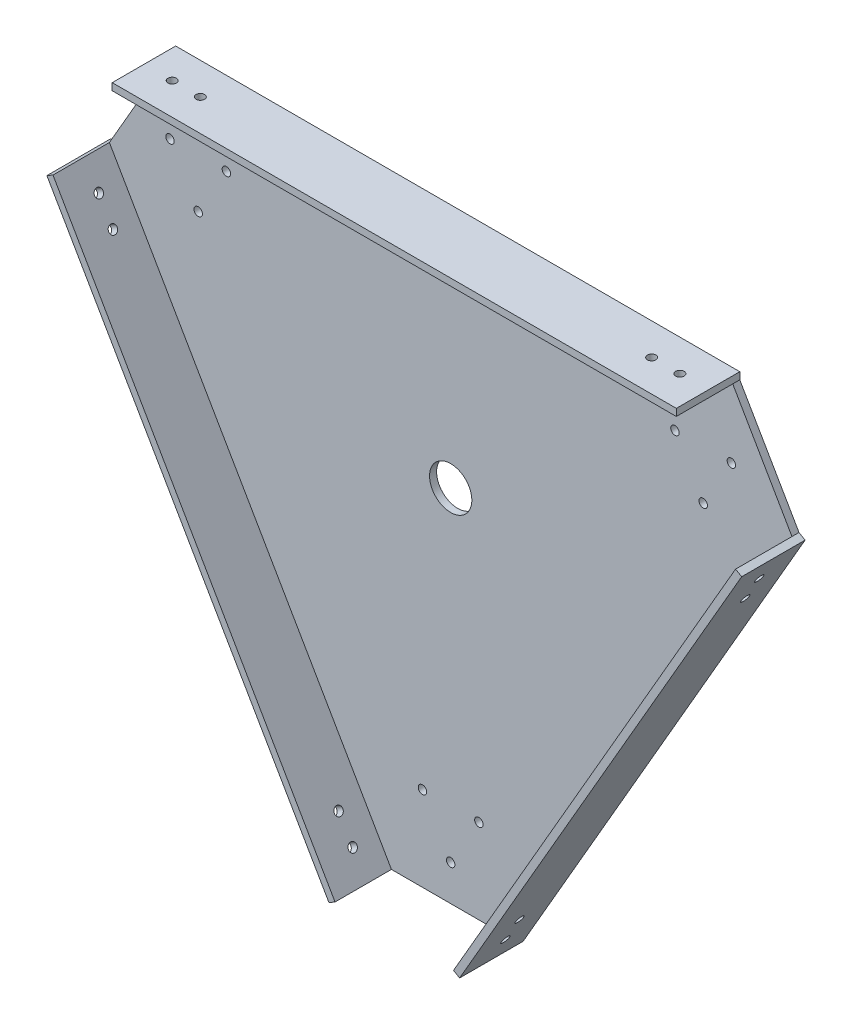
SolidWorks part; units mm, degrees
ref_plane "Спереди" through (0, 0, 0) normal (0, 0, 1) x (1, 0, 0)
ref_plane "Сверху" through (0, 0, 0) normal (0, 1, 0) x (1, 0, 0)
ref_plane "Справа" through (0, 0, 0) normal (1, 0, 0) x (0, 0, -1)
sketch "Эскиз1" plane through (0, 0, 0) normal (0, 0, 1) x (1, 0, 0)
  line L0 (0, 0) -> (21, 36.3731)
  line L1 (21, 36.3731) -> (221, 36.3731)
  line L2 (221, 36.3731) -> (242, 0)
  line L3 (242, 0) -> (142, -173.2051)
  line L4 (142, -173.2051) -> (100, -173.2051)
  line L5 (100, -173.2051) -> (0, 0)
  line L7 (31.4812, -5.474) -> (21.4812, 11.8465) construction
  line L8 (21.4812, 11.8465) -> (41.4812, 11.8465) construction
  line L9 (41.4812, 11.8465) -> (31.4812, -5.474) construction
  line L10 (21.4812, 11.8465) -> (10.5, 18.1865) construction
  line L11 (220.5188, 11.8465) -> (231.5, 18.1865) construction
  line L12 (210.5188, -5.474) -> (200.5188, 11.8465) construction
  line L13 (200.5188, 11.8465) -> (220.5188, 11.8465) construction
  line L14 (220.5188, 11.8465) -> (210.5188, -5.474) construction
  line L15 (121, -160.5251) -> (111, -143.2046) construction
  line L16 (111, -143.2046) -> (131, -143.2046) construction
  line L17 (131, -143.2046) -> (121, -160.5251) construction
  line L18 (121, -160.5251) -> (121, -173.2051) construction
  line L19 (121, -173.2051) -> (121, 36.3731) construction
  line L20 (10.5, 18.1865) -> (192, -86.6025) construction
  circle A0 centre (21.4812, 11.8465) radius 1.5
  circle A1 centre (41.4812, 11.8465) radius 1.5
  circle A2 centre (31.4812, -5.474) radius 1.5
  circle A3 centre (200.5188, 11.8465) radius 1.5
  circle A4 centre (220.5188, 11.8465) radius 1.5
  circle A5 centre (210.5188, -5.474) radius 1.5
  circle A6 centre (111, -143.2046) radius 1.5
  circle A7 centre (131, -143.2046) radius 1.5
  circle A8 centre (121, -160.5251) radius 1.5
  circle A9 centre (121, -45.6107) radius 7.5
  point P27 (121, -45.6107)
  dimension "D5" = 3
  dimension "D8" = 15
  dimension "D1" = 42
  dimension "D2" = 60
  dimension "D3" = 60
  dimension "D4" = 200
  dimension "D6" = 12.68
  dimension "D7" = 20
extrude "Бобышка-Вытянуть1" add sketch "Эскиз1" along normal blind 2.5
sketch "Эскиз2" plane through (0, 0, 0) normal (0, 0, -1) x (-1, 0, 0)
  line L0 (0, 0) -> (2.1651, -1.25)
  line L1 (2.1651, -1.25) -> (-97.8349, -174.4551)
  line L2 (-97.8349, -174.4551) -> (-100, -173.2051)
  line L3 (0, 0) -> (-100, -173.2051) construction
  line L4 (-21, 36.3731) -> (-21, 38.8731)
  line L5 (-21, 38.8731) -> (-221, 38.8731)
  line L6 (-221, 38.8731) -> (-221, 36.3731)
  line L7 (-242, 0) -> (-244.1651, -1.25)
  line L8 (-244.1651, -1.25) -> (-144.1651, -174.4551)
  line L9 (-144.1651, -174.4551) -> (-142, -173.2051)
  line L10 (-142, -173.2051) -> (-242, 0) construction
  line L11 (-221, 36.3731) -> (-21, 36.3731) construction
  line L12 (-242, 0) -> (-142, -173.2051)
  line L13 (-100, -173.2051) -> (0, 0)
  line L14 (-21, 36.3731) -> (-221, 36.3731)
  dimension "D1" = 2.5
extrude "Бобышка-Вытянуть2" add sketch "Эскиз2" against normal blind 22.5
sketch "Эскиз3" plane through (0, 38.8731, 0) normal (0, 1, 0) x (1, 0, 0)
  line L0 (211, -22.5) -> (211, 0) construction
  line L1 (21, -22.5) -> (221, -22.5) construction
  line L2 (21, 0) -> (221, 0) construction
  line L3 (221, -22.5) -> (221, 0) construction
  line L4 (201, -22.5) -> (201, 0) construction
  line L5 (41, -22.5) -> (41, 0) construction
  line L6 (31, -22.5) -> (31, 0) construction
  line L7 (21, -22.5) -> (21, 0) construction
  circle A0 centre (211, -11.25) radius 1.5
  circle A1 centre (201, -11.25) radius 1.5
  circle A2 centre (41, -11.25) radius 1.5
  circle A3 centre (31, -11.25) radius 1.5
  dimension "D1" = 3
  dimension "D2" = 10
  dimension "D5" = 10
  dimension "D7" = 10
  dimension "D3" = 2
  dimension "D4" = 2
  dimension "D6" = 2
extrude "Вырез-Вытянуть1" cut sketch "Эскиз3" against normal up to next
sketch "Эскиз6" plane through (183.6651, -106.0391, 0) normal (0.866, -0.5, 0) x (0, 0, -1)
  line L0 (-22.5, -69) -> (0, -69) construction
  line L1 (-22.5, -59) -> (0, -59) construction
  line L2 (-22.5, 101) -> (0, 101) construction
  line L3 (-22.5, 111) -> (0, 111) construction
  line L4 (0, 121) -> (0, -79) construction
  line L5 (-22.5, 121) -> (-22.5, -79) construction
  line L6 (-22.5, 121) -> (0, 121) construction
  line L7 (-22.5, -79) -> (0, -79) construction
  circle A3 centre (-11.25, 111) radius 1.5
  circle A4 centre (-11.25, 101) radius 1.5
  circle A5 centre (-11.25, -59) radius 1.5
  circle A6 centre (-11.25, -69) radius 1.5
  dimension "D1" = 2
  dimension "D6" = 3
  dimension "D2" = 10
  dimension "D3" = 10
  dimension "D5" = 10
  dimension "D4" = 2
extrude "Вырез-Вытянуть2" cut sketch "Эскиз6" against normal up to next
sketch "Эскиз7" plane through (-2.1651, -1.25, 0) normal (-0.866, -0.5, 0) x (0, 0, 1)
  line L0 (22.5, 0) -> (0, 0) construction
  line L1 (22.5, -200) -> (22.5, 0) construction
  line L2 (0, -20) -> (22.5, -20) construction
  line L3 (0, -10) -> (22.5, -10) construction
  line L4 (0, -200) -> (0, 0) construction
  line L5 (0, -190) -> (22.5, -190) construction
  line L6 (0, -180) -> (22.5, -180) construction
  line L7 (22.5, -200) -> (0, -200) construction
  circle A0 centre (11.25, -10) radius 1.5
  circle A1 centre (11.25, -20) radius 1.5
  circle A4 centre (11.25, -180) radius 1.5
  circle A5 centre (11.25, -190) radius 1.5
  dimension "D2" = 3
  dimension "D1" = 10
  dimension "D3" = 10
  dimension "D5" = 10
  dimension "D4" = 2
extrude "Вырез-Вытянуть3" cut sketch "Эскиз7" against normal up to next
